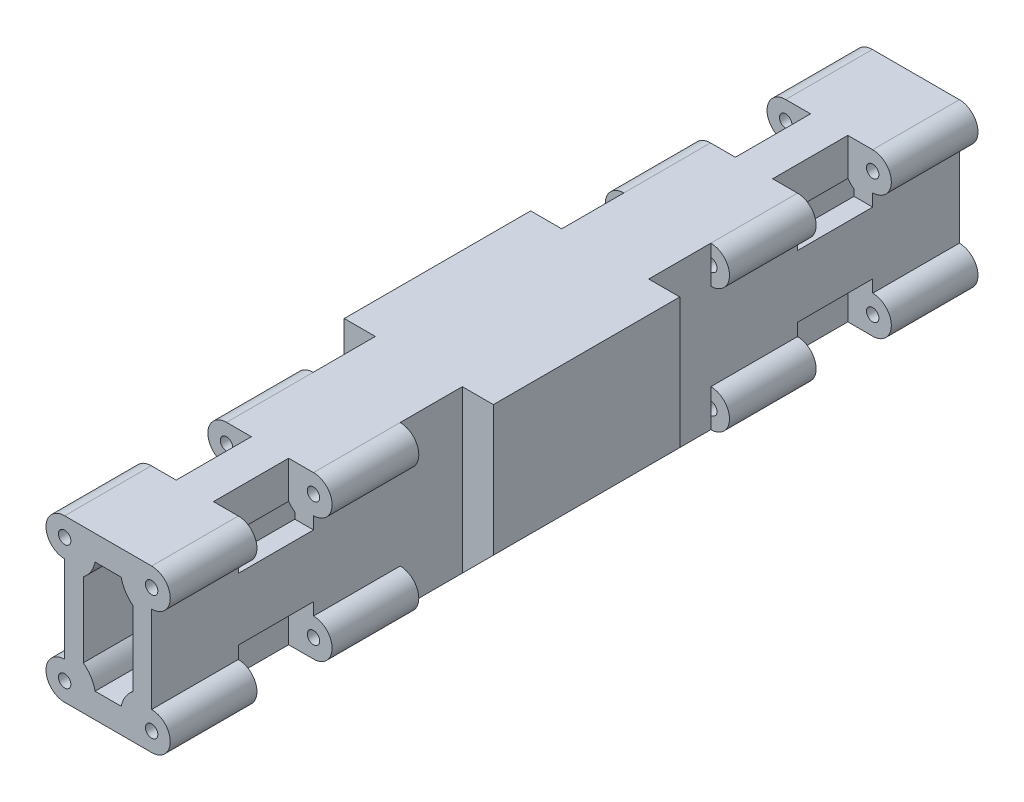
SolidWorks part; units mm, degrees
material "ABS"
ref_plane "Спереди" through (0, 0, 0) normal (0, 0, 1) x (1, 0, 0)
ref_plane "Сверху" through (0, 0, 0) normal (0, 1, 0) x (1, 0, 0)
ref_plane "Справа" through (0, 0, 0) normal (1, 0, 0) x (0, 0, -1)
sketch "Эскиз1" plane through (0, 0, 0) normal (0, 0, 1) x (1, 0, 0)
  line L0 (0, 30.7154) -> (0, -31.2898) construction
  line L2 (12, -13.2872) -> (-12, -13.2872)
  line L3 (12, -13.2872) -> (12, 12.7128)
  line L4 (12, 12.7128) -> (-12, 12.7128)
  line L5 (-12, -13.2872) -> (-12, 12.7128)
  line L6 (12, -13.2872) -> (-12, 12.7128) construction
  line L7 (12, 12.7128) -> (-12, -13.2872) construction
  point P3 (0, -0.2872)
  dimension "D1" = 24
  dimension "D2" = 26
extrude "Бобышка-Вытянуть1" add sketch "Эскиз1" along normal mid plane 130
sketch "Эскиз7" plane through (0, 0, 65) normal (0, 0, 1) x (1, 0, 0)
  line L1 (-12, -13.2872) -> (-7, -13.2872)
  line L2 (-12, -13.2872) -> (-12, 12.7128)
  line L3 (-12, 12.7128) -> (-7, 12.7128)
  line L4 (-7, -13.2872) -> (-7, 12.7128)
  dimension "D1" = 26
  dimension "D2" = 5
extrude "Вырез-Вытянуть5" cut sketch "Эскиз7" against normal blind 50
sketch "Эскиз4" plane through (0, 0, 65) normal (0, 0, 1) x (1, 0, 0)
  line L1 (-7, -13.2872) -> (-7, 12.7128) construction
  line L2 (-12, -13.2872) -> (-7, -13.2872) construction
  circle A0 centre (-7, 9.7128) radius 3
  circle A1 centre (-7, -10.2872) radius 3
  line M8 (-7, 12.7128) -> (-7, -13.2872)
  dimension "D1" = 6
  dimension "D2" = 20
  dimension "D3" = 3
extrude "Бобышка-Вытянуть3" add sketch "Эскиз4" against normal blind 40 contours A1 M8 | A1 M8 | A0
sketch "Эскиз5" plane through (-7, 0, 0) normal (-1, 0, 0) x (0, 0, 1)
  line L5 (25, -13.2872) -> (65, -13.2872) construction
  line L6 (38.95, -13.2872) -> (51.05, -13.2872)
  line L11 (38.95, -13.2872) -> (38.95, -5.2872)
  line L12 (38.95, -5.2872) -> (51.05, -5.2872)
  line L13 (51.05, -13.2872) -> (51.05, -5.2872)
  line L19 (65, 6.7128) -> (65, 12.7128) construction
  line L29 (38.95, 4.7128) -> (51.05, 4.7128)
  line L30 (38.95, 4.7128) -> (38.95, 12.7128)
  line L31 (38.95, 12.7128) -> (51.05, 12.7128)
  line L32 (51.05, 4.7128) -> (51.05, 12.7128)
  line L33 (25, 12.7128) -> (65, 12.7128) construction
  dimension "D1" = 12.1
  dimension "D2" = 8
  dimension "D4" = 8
  dimension "D3" = 13.95
extrude "Вырез-Вытянуть3" cut sketch "Эскиз5" against normal mid plane 8
sketch "Эскиз6" plane through (0, 0, 65) normal (0, 0, 1) x (1, 0, 0)
  circle A0 centre (-7, 9.7128) radius 1
  circle A1 centre (-7, -10.2872) radius 1
  dimension "D1" = 2
extrude "Вырез-Вытянуть4" cut sketch "Эскиз6" against normal blind 40
mirror "Зеркальное отражение1" about plane through (0, 0, 0) normal (0, 0, 1) of "Вырез-Вытянуть5", "Вырез-Вытянуть4", "Вырез-Вытянуть3", "Бобышка-Вытянуть3"
mirror "Зеркальное отражение2" about plane through (0, 0, 0) normal (1, 0, 0) of "Зеркальное отражение1", "Вырез-Вытянуть5", "Бобышка-Вытянуть3", "Вырез-Вытянуть3", "Вырез-Вытянуть4"
sketch "Эскиз9" plane through (0, 0, 0) normal (0, 0, 1) x (1, 0, 0)
  line L0 (0, 14.7189) -> (0, -15.9167) construction
  line L1 (-7, 10.7128) -> (-7, 8.7128) construction
  line L2 (7, 10.7128) -> (7, 8.7128) construction
  line L3 (-7, -9.2872) -> (-7, -11.2872) construction
  line L4 (7, -9.2872) -> (7, -11.2872) construction
  line L5 (-4, 5.7128) -> (-4, -6.2872)
  line L6 (-2.101, -9.2872) -> (2.101, -9.2872)
  line L7 (4, -6.2872) -> (4, 5.7128)
  line L8 (-2.101, 8.7128) -> (2.101, 8.7128)
  line L9 (7, 12.7128) -> (-7, 12.7128) construction
  line L10 (-7, -7.2872) -> (-7, 6.7128) construction
  line L11 (-7, -13.2872) -> (7, -13.2872) construction
  circle A0 centre (-7, 9.7128) radius 5
  circle A1 centre (7, 9.7128) radius 5
  circle A2 centre (-7, -10.2872) radius 5
  circle A3 centre (7, -10.2872) radius 5
  dimension "D1" = 10
  dimension "D2" = 4
  dimension "D3" = 3
  dimension "D4" = 4
extrude "Вырез-Вытянуть7" cut sketch "Эскиз9" against normal through all both and the other way through all contours L0 L8 A0 L5 A2 L6 | L8 L0 L6 A3 L7 A1
sketch "Эскиз10" plane through (0, 0, 15) normal (0, 0, 1) x (1, 0, 0)
  line L0 (12, 12.7128) -> (12, -13.2872) construction
  line L2 (-7, -13.2872) -> (7, -13.2872) construction
  line L4 (-12, 12.7128) -> (-12, -13.2872) construction
  line L5 (12, 12.7128) -> (12, -8.2872)
  line L6 (-12, -8.2872) -> (-7, -13.2872)
  line L7 (-7, -13.2872) -> (7, -13.2872)
  line L8 (12, -8.2872) -> (7, -13.2872)
  line L9 (-12, 12.7128) -> (-12, -8.2872)
  line L10 (-12, -8.2872) -> (-12, -13.2872)
  line L11 (-12, -13.2872) -> (-7, -13.2872)
  line L12 (7, -13.2872) -> (12, -13.2872)
  line L13 (12, -13.2872) -> (12, -8.2872)
  line M4 (-12, 12.7128) -> (-12, -13.2872)
  line M5 (-12, -13.2872) -> (-7, -13.2872)
extrude "Вырез-Вытянуть8" cut sketch "Эскиз10" against normal up to next contours L6 M4 M5 | L12 L13 L8
equation "\"D4@Эскиз5\"=\"D2@Эскиз5\""
equation "\"D4@Эскиз9\"=\"D2@Эскиз9\""
